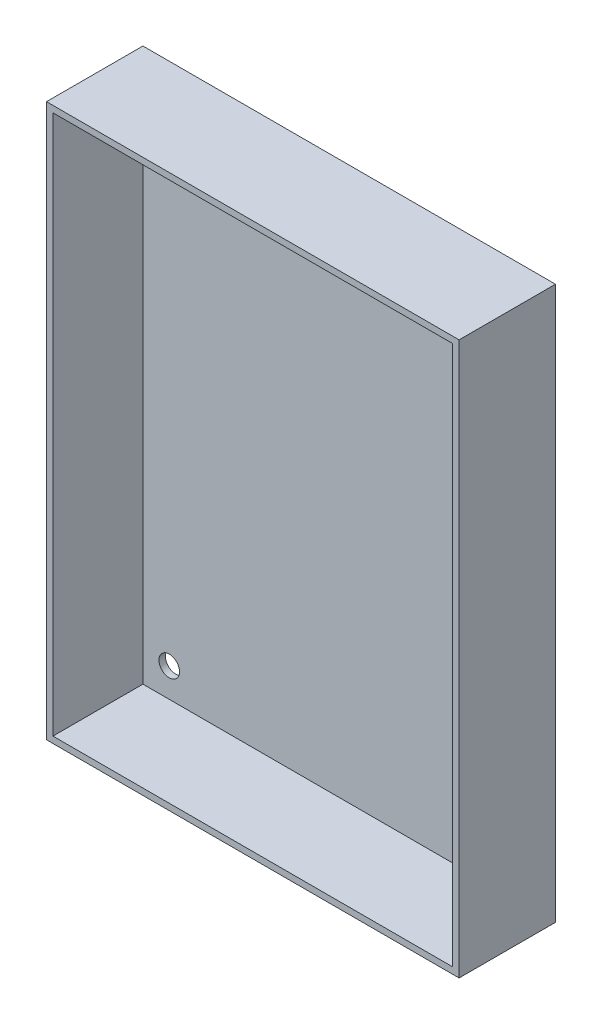
SolidWorks part; units mm, degrees
material "Ст 3 сп 5 ГОСТ 380-94"
ref_plane "Спереди" through (0, 0, 0) normal (0, 0, 1) x (1, 0, 0)
ref_plane "Сверху" through (0, 0, 0) normal (0, 1, 0) x (1, 0, 0)
ref_plane "Справа" through (0, 0, 0) normal (1, 0, 0) x (0, 0, -1)
sketch "Эскиз1" plane through (0, 0, 0) normal (0, 0, 1) x (1, 0, 0)
  line L1 (32.1, -43) -> (-32.1, -43)
  line L2 (32.1, -43) -> (32.1, 43)
  line L3 (32.1, 43) -> (-32.1, 43)
  line L4 (-32.1, -43) -> (-32.1, 43)
  line L5 (32.1, -43) -> (-32.1, 43) construction
  line L6 (32.1, 43) -> (-32.1, -43) construction
  point P0 (0, 0)
extrude "Бобышка-Вытянуть1" add sketch "Эскиз1" along normal blind 15
sketch "Эскиз2" plane through (0, 0, 15) normal (0, 0, 1) x (1, 0, 0)
  line L1 (31.1, -42) -> (-31.1, -42)
  line L2 (31.1, -42) -> (31.1, 42)
  line L3 (31.1, 42) -> (-31.1, 42)
  line L4 (-31.1, -42) -> (-31.1, 42)
  line L5 (31.1, -42) -> (-31.1, 42) construction
  line L6 (31.1, 42) -> (-31.1, -42) construction
  point P0 (0, 0)
extrude "Вырез-Вытянуть1" cut sketch "Эскиз2" against normal blind 14
sketch "Эскиз4" plane through (0, 0, 0) normal (0, 0, -1) x (-1, 0, 0)
  line L0 (-27, 0) -> (-27, 62.2231) construction
  line L1 (27, 0) -> (27, 56.024) construction
  line L2 (-27, 37.5) -> (-24.7344, 37.5) construction
  line L3 (27, 37.5) -> (26.4846, 37.5) construction
  line L4 (-27, -37.5) -> (-22.9334, -37.5) construction
  line L5 (27, -37.5) -> (24.4361, -37.5) construction
  circle A0 centre (-27, 37.5) radius 1.6
  circle A1 centre (27, 37.5) radius 1.6
  circle A2 centre (-27, -37.5) radius 1.6
  circle A3 centre (27, -37.5) radius 1.6
  point P13 (0, 0)
  dimension "D1" = 27
  dimension "D2" = 27
  dimension "D3" = 37.5
  dimension "D4" = 37.5
  dimension "D5" = 37.5
  dimension "D6" = 37.5
extrude "Вырез-Вытянуть2" cut sketch "Эскиз4" against normal blind 1
